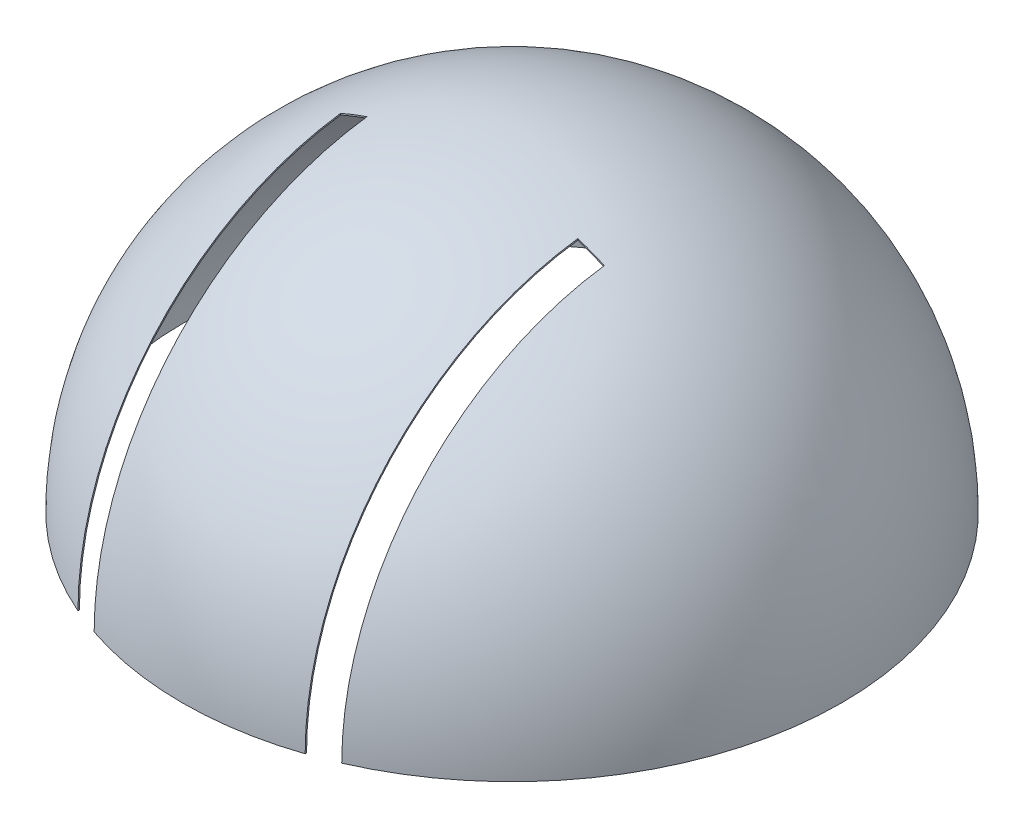
SolidWorks part; units mm, degrees
material "AISI 316 Отожженная нержавеющая сталь. полоса (SS)"
ref_plane "Спереди XY" through (0, 0, 0) normal (0, 0, 1) x (1, 0, 0)
ref_plane "Сверху XZ" through (0, 0, 0) normal (0, 1, 0) x (1, 0, 0)
ref_plane "Справа ZY" through (0, 0, 0) normal (1, 0, 0) x (0, 0, -1)
sketch "Эскиз1" plane through (0, 0, 0) normal (0, 1, 0) x (1, 0, 0)
  line L0 (-250, 0) -> (250, 0)
  arc A0 (250, 0) -> (-250, 0) centre (0, 0) ccw
  dimension "D1" = 250
revolve "Повернуть1" add sketch "Эскиз1" angle 180 about L0
shell "Оболочка1" thickness 1
sketch "Эскиз2" plane through (0, 0, 0) normal (0, 1, 0) x (1, 0, 0)
  line L0 (0, 263.6367) -> (0, -293.9158) construction
  line L1 (0, -250) -> (282.9527, -250) construction
  line L2 (-80, -250) -> (-100, -250)
  line L3 (80, -250) -> (100, -250)
  line L4 (80, -250) -> (80, -30)
  line L5 (80, -30) -> (100, -30)
  line L6 (100, -250) -> (100, -30)
  line L7 (-100, -250) -> (-100, -30)
  line L8 (-80, -30) -> (-100, -30)
  line L9 (-80, -250) -> (-80, -30)
  circle A0 centre (0, 0) radius 250 construction
  dimension "D1" = 20
  dimension "D2" = 80
  dimension "D3" = 30
extrude "Вырез-Вытянуть1" cut sketch "Эскиз2" along normal through all
